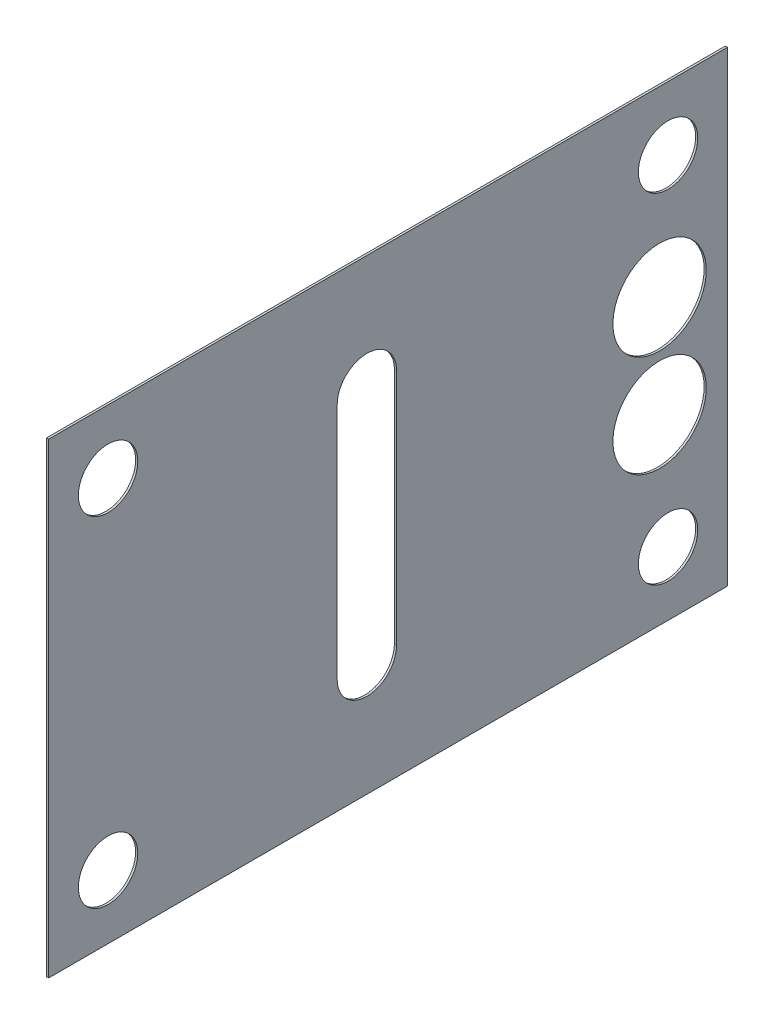
SolidWorks part; units mm, degrees
material "Low Carbon Steel"
ref_plane "Front Plane" through (0, 0, 0) normal (0, 0, 1) x (1, 0, 0)
ref_plane "Top Plane" through (0, 0, 0) normal (0, 1, 0) x (1, 0, 0)
ref_plane "Right Plane" through (0, 0, 0) normal (1, 0, 0) x (0, 0, -1)
sketch "Sketch1" plane through (0, 0, 0) normal (1, 0, 0) x (0, 0, -1)
  line L0 (-80, -55) -> (80, 55) construction
  line L1 (-80, 55) -> (80, 55)
  line L2 (-80, 55) -> (-80, -55)
  line L3 (-80, -55) -> (80, -55)
  line L4 (80, 55) -> (80, -55)
  dimension "D1" = 160
  dimension "D2" = 110
extrude "Boss-Extrude1" add sketch "Sketch1" along normal blind 0.508
hole_wizard "M12 Clearance Hole1" positions "Sketch2" profile "Sketch3" hole size "M12" standard "Peddi DIN" end condition through all
sketch "Sketch2" plane through (0.508, 0, 0) normal (1, 0, 0) x (0, 0, -1)
  line L0 (-66, 40) -> (66, 40) construction
  line L1 (66, 40) -> (66, -40) construction
  line L2 (66, -40) -> (-66, -40) construction
  line L3 (-66, -40) -> (66, 40) construction
  point P0 (-66, 40)
  point P2 (66, 40)
  point P4 (66, -40)
  point P6 (-66, -40)
  dimension "D1" = 80
  dimension "D2" = 132
sketch "Sketch3" plane through (0.508, 40, 66) normal (0, 1, 0) x (0, 0, -1)
  line L0 (0, 0) -> (0, 0.508)
  line L1 (0, 0.508) -> (7, 0.508)
  line L2 (7, 0.508) -> (7, 0)
  line L5 (7, 0) -> (0, 0)
  line L11 (0, -6.35) -> (0, 107.95) construction
  dimension "Thru Hole Dia." = 14
  dimension "Thru Hole Depth" = 0.508
sketch "Sketch4" plane through (0.508, 0, 0) normal (1, 0, 0) x (0, 0, -1)
  line L0 (-5, 28) -> (-5, -28) construction
  line L1 (2, 28) -> (2, -28)
  line L2 (-12, 28) -> (-12, -28)
  line L3 (-5, 0) -> (0, 0) construction
  arc A0 (2, 28) -> (-12, 28) centre (-5, 28) ccw
  arc A1 (-12, -28) -> (2, -28) centre (-5, -28) ccw
  circle A2 centre (66, 40) radius 7 construction
  point P2 (-5, 0)
  dimension "D3" = 71
  dimension "D1" = 14
  dimension "D2" = 56
extrude "Cut-Extrude1" cut sketch "Sketch4" against normal through all
hole_wizard "M20 Clearance Hole1" positions "Sketch5" profile "Sketch6" hole size "M20" standard "Peddi DIN" end condition through all
sketch "Sketch5" plane through (0.508, 0, 0) normal (1, 0, 0) x (0, 0, -1)
  line L0 (64, 12) -> (64, -12) construction
  line L2 (0, 0) -> (64, 0) construction
  circle A0 centre (66, 40) radius 7 construction
  point P0 (64, 12)
  point P5 (64, -12)
  dimension "D2" = 2
  dimension "D1" = 28
sketch "Sketch6" plane through (0.508, 12, -64) normal (0, 1, 0) x (0, 0, -1)
  line L0 (0, 0) -> (0, 0.508)
  line L1 (0, 0.508) -> (11, 0.508)
  line L2 (11, 0.508) -> (11, 0)
  line L5 (11, 0) -> (0, 0)
  line L11 (0, -6.35) -> (0, 107.95) construction
  dimension "Thru Hole Dia." = 22
  dimension "Thru Hole Depth" = 0.508
other "Freeze***"
